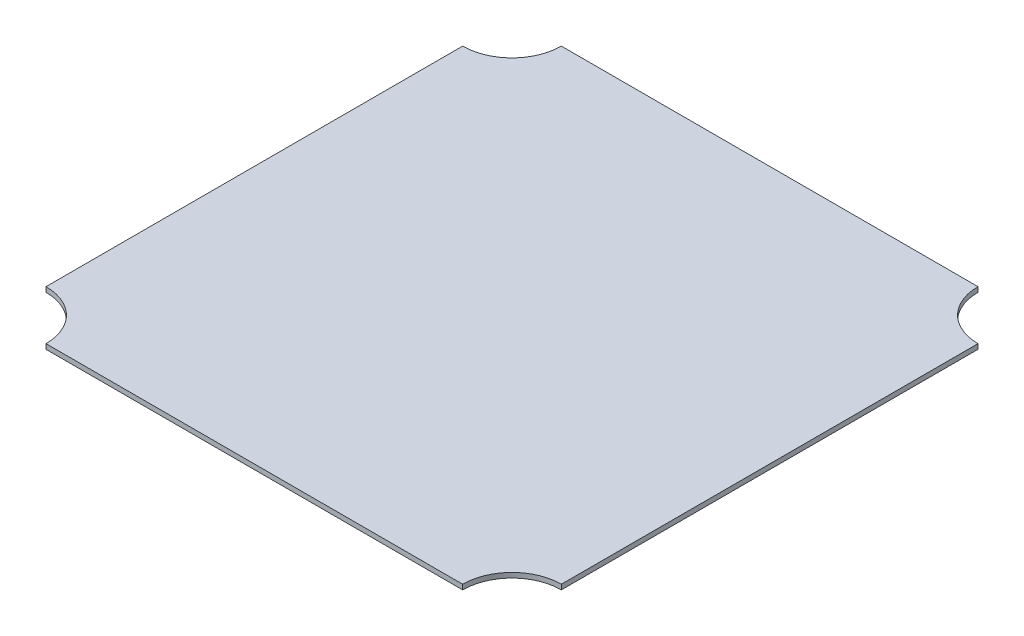
SolidWorks part; units mm, degrees
material "有机玻璃 (TM) GS 丙烯酸铸钣"
ref_plane "前视基准面" through (0, 0, 0) normal (0, 0, 1) x (1, 0, 0)
ref_plane "上视基准面" through (0, 0, 0) normal (0, 1, 0) x (1, 0, 0)
ref_plane "右视基准面" through (0, 0, 0) normal (1, 0, 0) x (0, 0, -1)
other "Configuration Table"
sketch "草图2" plane through (0, 0, 0) normal (0, 1, 0) x (1, 0, 0)
  line L0 (0, 0) -> (0, 149.2038) construction
  line L5 (211.7834, 0) -> (-211.7834, 0) construction
  line L6 (-261, -211) -> (-261, 211)
  line L7 (-211, 261) -> (211, 261)
  line L8 (-211, -261) -> (211, -261)
  line L9 (261, -211) -> (261, 211)
  arc A2 (-261, 211) -> (-211, 261) centre (-261, 261) ccw
  arc A3 (-261, -211) -> (-211, -261) centre (-261, -261) cw
  arc A4 (261, -211) -> (211, -261) centre (261, -261) ccw
  arc A5 (261, 211) -> (211, 261) centre (261, 261) cw
  point P6 (261, 0)
  point P10 (-261, 0)
  point P11 (0, 261)
  point P20 (0, -261)
  dimension "D1" = 261
  dimension "D3" = 50
  dimension "D2" = 261
extrude "凸台-拉伸1" add sketch "草图2" along normal blind 5
